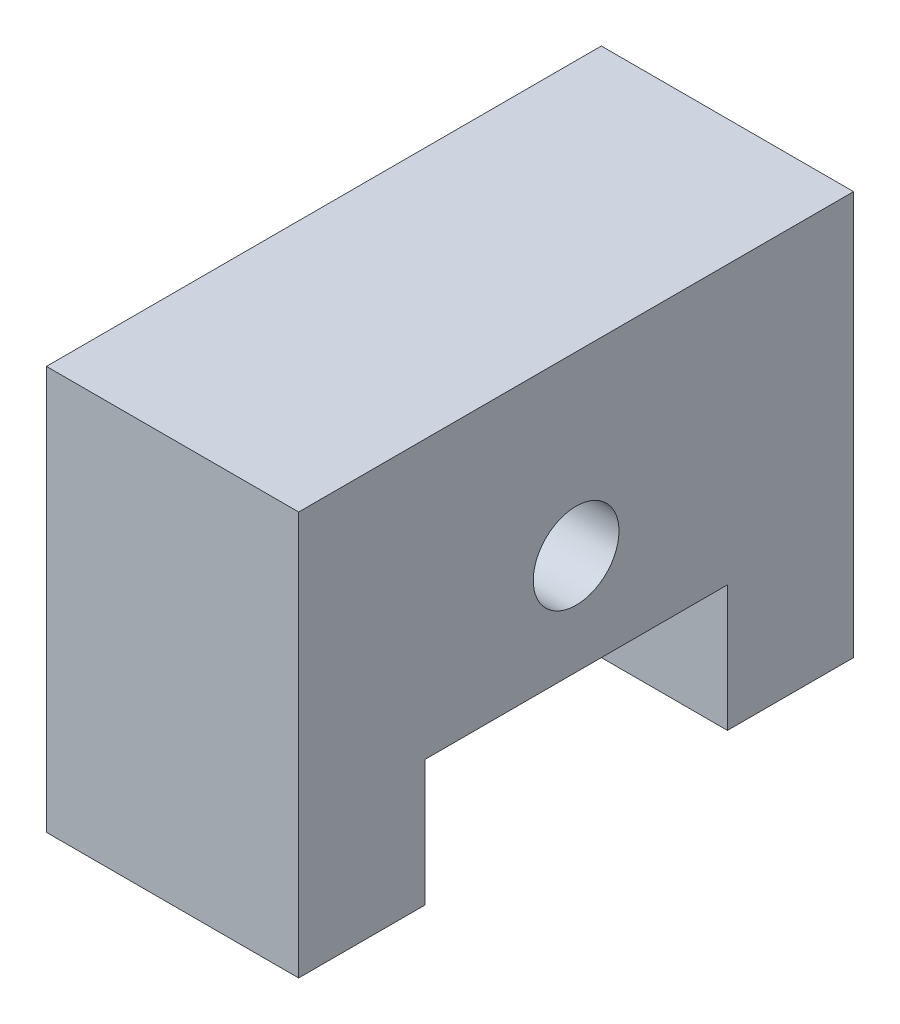
SolidWorks part; units mm, degrees
material "AISI 1020"
ref_plane "Front Plane" through (0, 0, 0) normal (0, 0, 1) x (1, 0, 0)
ref_plane "Top Plane" through (0, 0, 0) normal (0, 1, 0) x (1, 0, 0)
ref_plane "Right Plane" through (0, 0, 0) normal (1, 0, 0) x (0, 0, -1)
sketch "Sketch1" plane through (0, 0, 0) normal (1, 0, 0) x (0, 0, -1)
  line L0 (0, 0) -> (0, 27.8788) construction
  line L1 (12, 10) -> (-12, 10)
  line L2 (-12, 10) -> (-12, 0)
  line L3 (-12, 0) -> (-22, 0)
  line L4 (-22, 0) -> (-22, 32)
  line L5 (-22, 32) -> (22, 32)
  line L6 (22, 0) -> (22, 32)
  line L7 (12, 0) -> (22, 0)
  line L8 (12, 10) -> (12, 0)
  point P10 (0, 32)
  point P13 (0, 10)
  dimension "D1" = 44
  dimension "D2" = 24
  dimension "D3" = 32
  dimension "D4" = 10
extrude "Boss-Extrude1" add sketch "Sketch1" along normal mid plane 20
hole_wizard "M8 Tapped Hole1" positions "Sketch2" profile "Sketch4" tap size "M8" standard "ISO"
sketch "Sketch2" plane through (10, 0, 0) normal (1, 0, 0) x (0, 0, -1)
  line L0 (22, 0) -> (22, 32) construction
  line L1 (12, 0) -> (22, 0) construction
  point P0 (0, 18)
  dimension "D1" = 22
  dimension "D2" = 18
sketch "Sketch4" plane through (10, 18, 0) normal (0, 1, 0) x (0, 0, -1)
  line L0 (0, 0) -> (0, 16.0429)
  line L1 (0, 16.0429) -> (3.4, 14)
  line L2 (3.4, 14) -> (3.4, 0)
  line L5 (3.4, 0) -> (0, 0)
  line L10 (0, 16.0429) -> (-3.4, 14) construction
  line L11 (0, -6.35) -> (0, 107.95) construction
  dimension "Tap Drill Dia." = 6.8
  dimension "Tap Drill Depth" = 14
  dimension "Drill Angle" = 118
cosmetic thread "Hole Thread1" parameters "D1"=10, "D2"=8
hole_wizard "M5 Tapped Hole1" positions "Sketch6" profile "Sketch7" tap size "M5" standard "ISO"
sketch "Sketch6" plane through (0, 0, 0) normal (0, -1, 0) x (-1, 0, 0)
  line L0 (0, 0) -> (13.8766, 0) construction
  point P0 (0, 17)
  point P2 (0, -17)
  dimension "D1" = 34
sketch "Sketch7" plane through (0, 0, -17) normal (1, 0, 0) x (0, 0, -1)
  line L0 (0, 0) -> (0, 13.2618)
  line L1 (0, 13.2618) -> (2.1, 12)
  line L2 (2.1, 12) -> (2.1, 0)
  line L5 (2.1, 0) -> (0, 0)
  line L10 (0, 13.2618) -> (-2.1, 12) construction
  line L11 (0, -6.35) -> (0, 107.95) construction
  dimension "Tap Drill Dia." = 4.2
  dimension "Tap Drill Depth" = 12
  dimension "Drill Angle" = 118
cosmetic thread "Hole Thread2" parameters "D1"=9, "D2"=5
cosmetic thread "Hole Thread3" parameters "D1"=9, "D2"=5
